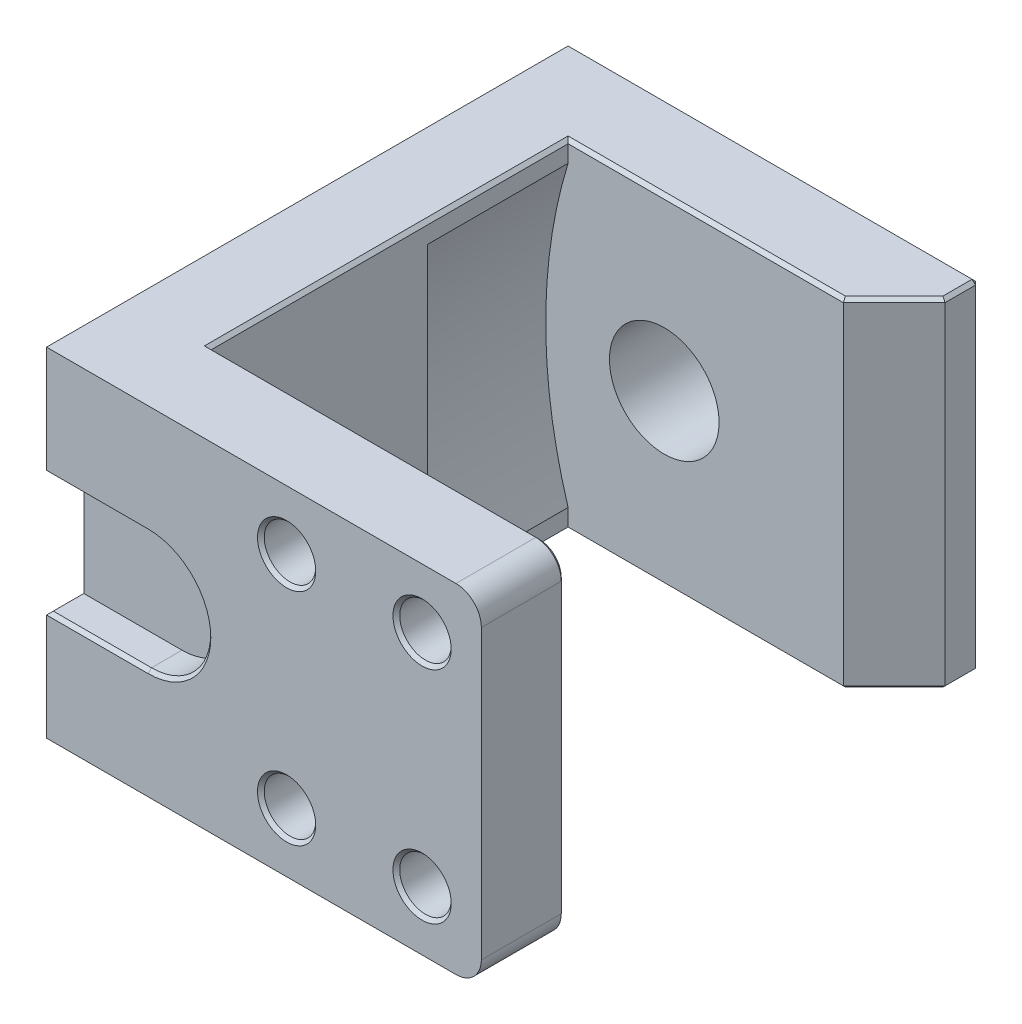
SolidWorks part; units mm, degrees
other "标注1"
sketch "草图9" plane through (-10.48, 10, -1.55) normal (-0.4516, 0.1897, -0.8718) x (-0.888, 0, 0.4599)
material "7075-T6 (SN)"
ref_plane "前视基准面" through (0, 0, 0) normal (0, 0, 1) x (1, 0, 0)
ref_plane "上视基准面" through (0, 0, 0) normal (0, 1, 0) x (1, 0, 0)
ref_plane "右视基准面" through (0, 0, 0) normal (1, 0, 0) x (0, 0, -1)
sketch "草图1" plane through (0, 0, 0) normal (0, 0, 1) x (1, 0, 0)
  line L1 (13.5775, 0) -> (13.5775, 10)
  line L2 (13.5775, 0) -> (13.5775, -10)
  line L4 (-10.48, 0) -> (-10.48, 10)
  line L5 (-10.48, 10) -> (13.5775, 10)
  line L6 (13.5775, -10) -> (-10.48, -10)
  line L7 (-10.48, -10) -> (-10.48, 0)
  circle A0 centre (0, 0) radius 3.2375
extrude "凸台-拉伸1" add sketch "草图1" along normal blind 5
sketch "草图2" plane through (0, 0, 0) normal (0, 0, 1) x (1, 0, 0)
  circle A0 centre (0, 5.6) radius 1.265
  circle A1 centre (0, -5.6) radius 1.265
extrude "切除-拉伸1" cut sketch "草图2" along normal blind 2.85
chamfer "倒角1" distance 0.2 angle 45 2 edges at (1.265, -5.6, 0) (1.265, 5.6, 0)
sketch "草图5" plane through (0, 0, 0) normal (0, 0, 1) x (1, 0, 0)
  line L0 (-8.76, 7.275) -> (-10.48, 7.275)
  line L1 (-8.76, 7.275) -> (-8.76, -7.275)
  line L4 (-10.48, 10) -> (-10.48, -10) construction
  line L5 (-10.48, 7.275) -> (-10.48, -7.275)
  line L6 (-10.48, -7.275) -> (-8.76, -7.275)
extrude "凸台-拉伸2" add sketch "草图5" against normal blind 1.55 from surface at 0 starting at face at (-1.465, -5.6, 0)
chamfer "倒角2" distance 0.2 angle 45 4 edges at (-9.62, -7.275, -1.55) (-10.48, 0, -1.55) (-9.62, 7.275, -1.55) (-8.76, 0, -1.55)
fillet "圆角1" radius 0.15 4 edges at (-10.48, -7.275, -0.675) (-10.48, 7.275, -0.675) (-8.76, -7.275, -0.675) (-8.76, 7.275, -0.675)
sketch "草图6" plane through (0, 0, 0) normal (0, 0, 1) x (1, 0, 0)
  line L1 (13.5775, 10) -> (-10.48, 10) construction
  line L3 (-10.48, -10) -> (13.5775, -10) construction
  line L6 (-10.48, 10) -> (-5.68, 10)
  line L7 (-10.48, 10) -> (-10.48, -10)
  line L8 (-10.48, -10) -> (-5.68, -10)
  line L9 (-5.68, -10) -> (-5.68, 10)
extrude "凸台-拉伸3" add sketch "草图6" along normal blind 31
sketch "草图7" plane through (0, 0, 0) normal (0, 0, 1) x (1, 0, 0)
  line L1 (13.5775, 10) -> (-5.68, 10) construction
  line L2 (-6.3225, 10) -> (-6.3225, -10)
  line L3 (-5.68, -10) -> (13.5775, -10) construction
  line L9 (-6.3225, 10) -> (19.5775, 10)
  line L10 (19.5775, 10) -> (19.5775, -10)
  line L11 (19.5775, -10) -> (-6.3225, -10)
extrude "凸台-拉伸4" add sketch "草图7" against normal blind 4.92 from surface at 31 starting at face at (-8.08, 0, 31)
sketch "草图8" plane through (0, 0, 0) normal (0, 0, 1) x (1, 0, 0)
  circle A4 centre (3.6975, 6.5) radius 1.52
  circle A5 centre (11.6975, 6.5) radius 1.52
  circle A6 centre (11.6975, -6.5) radius 1.52
  circle A7 centre (3.6975, -6.5) radius 1.52
extrude "切除-拉伸2" cut sketch "草图8" against normal up to surface (4.92 mm away) from surface
chamfer "倒角3" distance 0.2 angle 45 4 edges at (5.2175, -6.5, 31) (13.2175, -6.5, 31) (13.2175, 6.5, 31) (5.2175, 6.5, 31)
sketch "草图10" plane through (0, 0, 0) normal (0, 0, 1) x (1, 0, 0)
  line L7 (19.5775, -10) -> (19.5775, 10)
  line L8 (19.5775, 10) -> (15.1975, 10)
  line L9 (19.5775, 10) -> (-10.48, 10) construction
  line L10 (15.1975, 10) -> (15.1975, -10)
  line L11 (-10.48, -10) -> (19.5775, -10) construction
  line L12 (15.1975, -10) -> (19.5775, -10)
extrude "切除-拉伸3" cut sketch "草图10" against normal up to surface (31 mm away) from surface at 31 up to face at (-5.8971, 0, 0) starting at face at (5.4175, -6.5, 31)
fillet "圆角2" radius 1.5 2 edges at (15.1975, -10, 28.54) (15.1975, 10, 28.54)
sketch "草图11" plane through (0, 0, 0) normal (0, 0, 1) x (1, 0, 0)
  line L2 (-4.48, 3.5) -> (-10.48, 3.5)
  line L5 (-10.48, 10) -> (-10.48, -10) construction
  line L6 (-10.48, 3.5) -> (-10.48, -3.5)
  line L7 (-10.48, -3.5) -> (-4.48, -3.5)
  arc A1 (-4.48, 3.5) -> (-4.48, -3.5) centre (-4.48, 0) cw
extrude "切除-拉伸4" cut sketch "草图11" against normal blind 2 from surface at 31 starting at face at (5.4175, -6.5, 31)
sketch "草图13" plane through (0, 0, 0) normal (0, 0, 1) x (1, 0, 0)
  line L3 (12.399, 10) -> (12.399, -10)
  line L4 (12.399, 10) -> (9.199, 10)
  line L5 (13.6975, 10) -> (-10.48, 10) construction
  line L6 (9.199, 10) -> (9.199, -10)
  line L7 (9.199, -10) -> (12.399, -10)
extrude "凸台-拉伸5" add sketch "草图13" along normal up to surface (5 mm away) from surface at 0 up to face at (3.2375, 0, 5) starting at face at (-5.8971, 0, 0)
chamfer "倒角5" distance 3 angle 45 1 edges at (13.5775, 0, 5)
sketch "草图14" plane through (0, 0, 0) normal (0, 0, 1) x (1, 0, 0)
  line L1 (13.6975, 10) -> (-10.48, 10) construction
  line L2 (-10.48, -10) -> (13.6975, -10) construction
  line L3 (-5.2843, 10) -> (-5.2843, -10)
  arc A4 (-5.2843, 10) -> (-5.2843, -10) centre (23, 0) ccw
extrude "切除-拉伸5" cut sketch "草图14" along normal blind 7 from surface at 5 starting at face at (2.4487, 0, 5)
chamfer "倒角7" distance 1.3 angle 45 1 edges at (-5.68, 0, 12)
chamfer "倒角8" distance 0.2 angle 45 22 edges at (1.5488, -10, 0) (1.5487, 10, 0) (2.4487, 10, 5) (2.4488, -10, 5) (-7.48, -3.5, 31) (-0.98, 0, 31) (-7.48, 3.5, 31) (4.0088, -10, 26.08) (14.7582, -9.5607, 26.08) (15.1975, 0, 26.08) (14.7582, 9.5607, 26.08) (-5.68, -10, 15.54) (4.0088, 10, 26.08) (-5.68, 10, 15.54) (12.0775, 10, 3.5) (13.5775, 10, 1) (13.5775, 0, 0) (13.5775, -10, 1) (12.0775, -10, 3.5) (-10.48, -3.5, 30) (-10.48, 0, 29) (-10.48, 3.5, 30)
